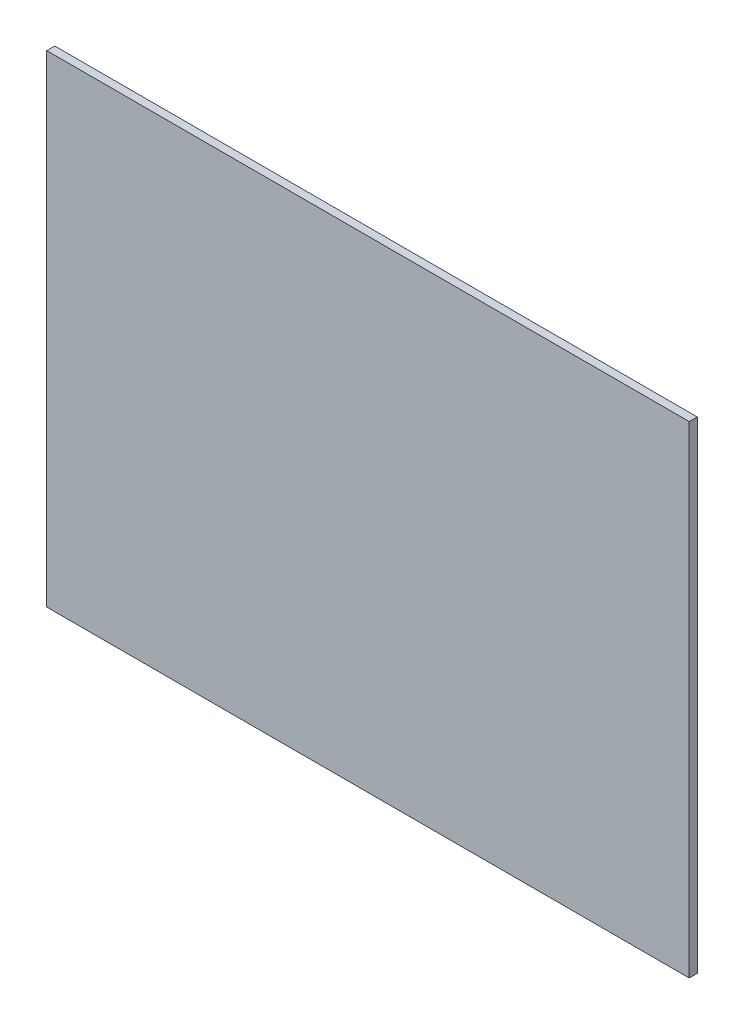
SolidWorks part; units mm, degrees
material "PE High Density"
ref_plane "Front Plane" through (0, 0, 0) normal (1, 0, 0) x (0, 1, 0)
ref_plane "Top Plane" through (0, 0, 0) normal (0, 0, 1) x (0, 1, 0)
ref_plane "Right Plane" through (0, 0, 0) normal (0, 1, 0) x (-1, 0, 0)
sketch "Sketch1" plane through (0, 0, 0) normal (0, 0, 1) x (0, 1, 0)
  line L1 (-30, 40) -> (30, 40)
  line L2 (-30, 40) -> (-30, -40)
  line L3 (-30, -40) -> (30, -40)
  line L4 (30, 40) -> (30, -40)
  line L5 (-30, 40) -> (30, -40) construction
  line L6 (-30, -40) -> (30, 40) construction
  point P0 (0, 0)
  dimension "D1" = 80
  dimension "D2" = 60
extrude "Boss-Extrude1" add sketch "Sketch1" against normal blind 1 contours L1 L4 L3 L2
scale "Scale1" scale about centroid uniform scaling yes scale factor 0.7
